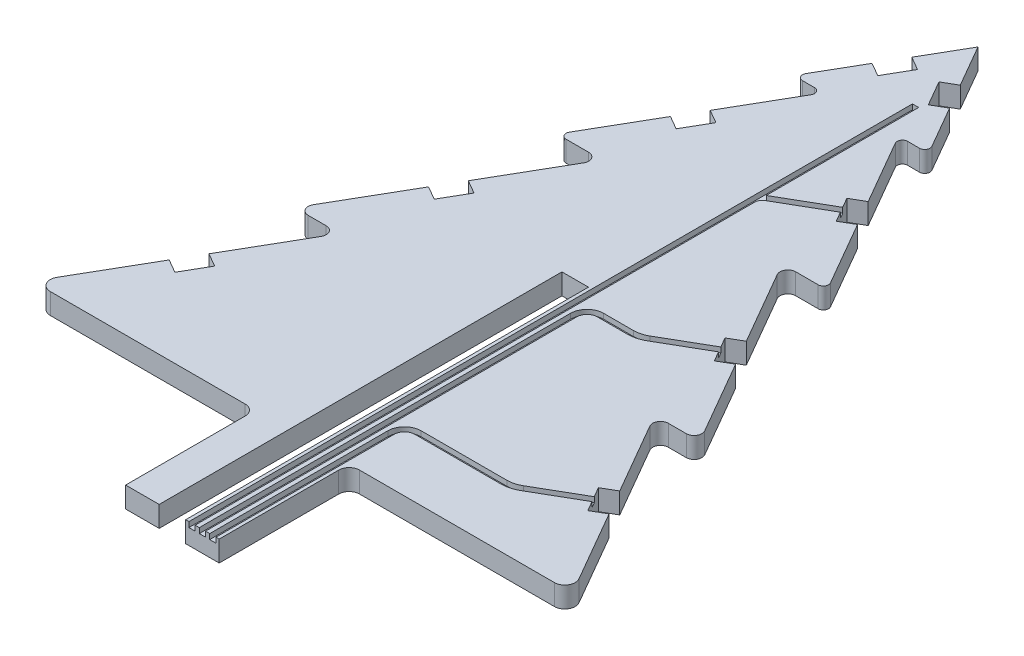
SolidWorks part; units mm, degrees
ref_plane "Plano frontal" through (0, 0, 0) normal (0, 0, 1) x (1, 0, 0)
ref_plane "Plano superior" through (0, 0, 0) normal (0, 1, 0) x (1, 0, 0)
ref_plane "Plano direito" through (0, 0, 0) normal (1, 0, 0) x (0, 0, -1)
sketch "Esboço1" plane through (0, 0, 0) normal (0, 1, 0) x (1, 0, 0)
  line L0 (0, 16.1772) -> (0, -226.058) construction
  line L1 (-9, -140) -> (9, -140)
  line L2 (0, -25) -> (-51.9615, -115)
  line L3 (-51.9615, -115) -> (51.9615, -115)
  line L4 (51.9615, -115) -> (0, -25)
  line L5 (0, 15) -> (-12.9904, -7.5)
  line L6 (-12.9904, -7.5) -> (12.9904, -7.5)
  line L7 (12.9904, -7.5) -> (0, 15)
  line L8 (0, 5) -> (-25.9808, -40)
  line L9 (-25.9808, -40) -> (25.9808, -40)
  line L10 (25.9808, -40) -> (0, 5)
  line L11 (0, -10) -> (-38.9711, -77.5)
  line L12 (-38.9711, -77.5) -> (38.9711, -77.5)
  line L13 (38.9711, -77.5) -> (0, -10)
  line L14 (-9, -140) -> (-9, -115)
  line L15 (9, -140) -> (9, -115)
  circle A0 centre (0, 0) radius 7.5 construction
  circle A1 centre (0, -25) radius 15 construction
  circle A2 centre (0, -55) radius 22.5 construction
  circle A3 centre (0, -85) radius 30 construction
  point P6 (0, 0)
  point P9 (0, -10)
  point P28 (0, -140)
  dimension "D2" = 15
  dimension "D6" = 30
  dimension "D9" = 45
  dimension "D11" = 60
  dimension "D1" = 0
  dimension "D3" = 25
  dimension "D4" = 90
  dimension "D5" = 90
  dimension "D7" = 30
  dimension "D8" = 90
  dimension "D10" = 90
  dimension "D12" = 30
  dimension "D13" = 18
  dimension "D14" = 55
extrude "Árvore" add sketch "Esboço1" along normal blind 4 contours L1 L15 L3 L14 | L12 L2 L3 L4 | L2 L12 L4 L9 | L9 L13 L11 L2 L4 | L12 L13 L9 L4 | L2 L9 L4 | L11 L12 L2 L9 | L13 L9 L10 L6 L8 L11 | L6 L10 L8 | L10 L6 L7 L5 L8
sketch "Esboço2" plane through (0, 4, 0) normal (0, 1, 0) x (1, 0, 0)
  line L0 (0, -33.105) -> (0, 19.5477) construction
  line L1 (0, 19.5477) -> (0, -147.1319) construction
  line L2 (-9, -140) -> (9, -140) construction
  line L3 (-2.55, -62.5) -> (2.55, -62.5)
  line L4 (-2.55, -62.5) -> (-2.55, -140)
  line L5 (-2.55, -140) -> (2.55, -140)
  line L6 (2.55, -62.5) -> (2.55, -140)
  line L7 (-2.55, -62.5) -> (2.55, -140) construction
  line L8 (-2.55, -140) -> (2.55, -62.5) construction
  point P3 (0, -101.25)
  dimension "D1" = 77.5
  dimension "D2" = 5.1
extrude "Encaixe" cut sketch "Esboço2" against normal blind 5
fillet "Filete2" radius 1 1 edges at (12.9904, 2, 7.5)
fillet "Filete3" radius 1 1 edges at (-12.9904, 2, 7.5)
fillet "Filete4" radius 1 1 edges at (-7.2169, 2, 7.5)
fillet "Filete5" radius 1 1 edges at (7.2169, 2, 7.5)
fillet "Filete6" radius 1 1 edges at (25.9808, 2, 40)
fillet "Filete7" radius 1 1 edges at (-25.9808, 2, 40)
fillet "Filete8" radius 1.5 1 edges at (17.3205, 2, 40)
fillet "Filete9" radius 1.5 1 edges at (-17.3205, 2, 40)
fillet "Filete10" radius 1.5 1 edges at (38.9711, 2, 77.5)
fillet "Filete11" radius 1.5 1 edges at (-38.9711, 2, 77.5)
fillet "Filete12" radius 2 1 edges at (51.9615, 2, 115)
fillet "Filete13" radius 2 1 edges at (-51.9615, 2, 115)
fillet "Filete14" radius 2 1 edges at (9, 2, 115)
fillet "Filete15" radius 2 1 edges at (-9, 2, 115)
fillet "Filete16" radius 1.5 1 edges at (30.3109, 2, 77.5)
fillet "Filete17" radius 1.5 1 edges at (-30.3109, 2, 77.5)
sketch "Esboço5" plane through (0, 4, 0) normal (0, 1, 0) x (1, 0, 0)
  line L0 (42.3195, -98.2995) -> (39.5195, -93.4497)
  line L1 (42.3195, -98.2995) -> (39.7214, -99.7995)
  line L2 (39.5195, -93.4497) -> (36.9214, -94.9497)
  line L3 (39.7214, -99.7995) -> (36.9214, -94.9497)
  line L4 (50.2295, -112) -> (31.6099, -79.75) construction
  line L5 (29.5446, -61.1728) -> (26.7446, -56.323)
  line L6 (29.5446, -61.1728) -> (26.9465, -62.6728)
  line L7 (26.7446, -56.323) -> (24.1465, -57.823)
  line L8 (26.9465, -62.6728) -> (24.1465, -57.823)
  line L9 (37.6721, -75.25) -> (18.6195, -42.25) construction
  line L10 (17.9997, -26.1765) -> (15.1997, -21.3267)
  line L11 (17.9997, -26.1765) -> (15.4017, -27.6765)
  line L12 (15.1997, -21.3267) -> (12.6017, -22.8267)
  line L13 (15.4017, -27.6765) -> (12.6017, -22.8267)
  line L14 (25.1147, -38.5) -> (8.0829, -9) construction
  line L15 (7.4619, 2.0757) -> (4.6619, 6.9254)
  line L16 (7.4619, 2.0757) -> (4.8638, 0.5757)
  line L17 (4.6619, 6.9254) -> (2.0638, 5.4254)
  line L18 (4.8638, 0.5757) -> (2.0638, 5.4254)
  line L19 (12.1244, -6) -> (0, 15) construction
  line L20 (0, 20.6146) -> (0, -144.6406) construction
  line L21 (-7.4619, 2.0757) -> (-4.6619, 6.9254)
  line L22 (-7.4619, 2.0757) -> (-4.8638, 0.5757)
  line L23 (-4.8638, 0.5757) -> (-2.0638, 5.4254)
  line L24 (-4.6619, 6.9254) -> (-2.0638, 5.4254)
  line L25 (-17.9997, -26.1765) -> (-15.1997, -21.3267)
  line L26 (-17.9997, -26.1765) -> (-15.4017, -27.6765)
  line L27 (-15.4017, -27.6765) -> (-12.6017, -22.8267)
  line L28 (-15.1997, -21.3267) -> (-12.6017, -22.8267)
  line L29 (-29.5446, -61.1728) -> (-26.7446, -56.323)
  line L30 (-29.5446, -61.1728) -> (-26.9465, -62.6728)
  line L31 (-26.9465, -62.6728) -> (-24.1465, -57.823)
  line L32 (-26.7446, -56.323) -> (-24.1465, -57.823)
  line L33 (-42.3195, -98.2995) -> (-39.5195, -93.4497)
  line L34 (-42.3195, -98.2995) -> (-39.7214, -99.7995)
  line L35 (-39.7214, -99.7995) -> (-36.9214, -94.9497)
  line L36 (-39.5195, -93.4497) -> (-36.9214, -94.9497)
  dimension "D1" = 5.6
  dimension "D2" = 3
  dimension "D3" = 15.82
  dimension "D4" = 3
  dimension "D5" = 5.6
  dimension "D6" = 16.255
  dimension "D7" = 3
  dimension "D8" = 5.6
  dimension "D9" = 14.23
  dimension "D10" = 3
  dimension "D11" = 5.6
  dimension "D12" = 9.325
extrude "Cortes do Led" cut sketch "Esboço5" against normal blind 10
sketch "Esboço6" plane through (0, 4, 0) normal (0, 1, 0) x (1, 0, 0)
  line L0 (2.55, -140) -> (9, -140) construction
  line L1 (3.175, -140) -> (4.375, -140)
  line L2 (3.175, -140) -> (3.175, -0.7885)
  line L3 (3.175, -0.7885) -> (4.375, -0.7885)
  line L4 (4.375, -140) -> (4.375, -0.7885)
  line L5 (2.55, -140) -> (2.55, -62.5) construction
  line L6 (5.175, -140) -> (6.375, -140)
  line L7 (5.175, -140) -> (5.175, -68.5981)
  line L8 (5.175, -68.5981) -> (6.375, -68.5981)
  line L9 (6.375, -140) -> (6.375, -68.5981)
  line L10 (7.175, -140) -> (8.375, -140)
  line L11 (7.175, -140) -> (7.175, -105.7249)
  line L12 (7.175, -105.7249) -> (8.375, -105.7249)
  line L13 (8.375, -140) -> (8.375, -105.7249)
  line L14 (36.9214, -94.9497) -> (39.7214, -99.7995) construction
  line L15 (38.0214, -96.855) -> (38.6214, -97.8942)
  line L16 (38.0214, -96.855) -> (29.3611, -101.855)
  line L17 (38.6214, -97.8942) -> (29.9611, -102.8942)
  line L19 (25.2465, -59.7283) -> (25.8465, -60.7675)
  line L20 (25.2465, -59.7283) -> (16.5863, -64.7283)
  line L21 (25.8465, -60.7675) -> (17.1863, -65.7675)
  line L22 (16.5863, -64.7283) -> (17.1863, -65.7675)
  line L23 (24.1465, -57.823) -> (26.9465, -62.6728) construction
  line L24 (13.7017, -24.732) -> (14.3017, -25.7712)
  line L25 (13.7017, -24.732) -> (3.3094, -30.732)
  line L26 (14.3017, -25.7712) -> (3.9094, -31.7712)
  line L27 (3.3094, -30.732) -> (3.9094, -31.7712)
  line L28 (12.6017, -22.8267) -> (15.4017, -27.6765) construction
  line L29 (3.1638, 3.5202) -> (3.7638, 2.4809)
  line L30 (3.1638, 3.5202) -> (1.7898, 2.7269)
  line L31 (3.7638, 2.4809) -> (2.3898, 1.6877)
  line L32 (1.7898, 2.7269) -> (2.3898, 1.6877)
  line L33 (2.0638, 5.4254) -> (4.8638, 0.5757) construction
  line L34 (29.3611, -101.855) -> (29.9611, -102.8942)
  line L35 (10.375, -102.5249) -> (26.8611, -102.5249)
  line L36 (10.375, -102.5249) -> (10.375, -103.7249)
  line L37 (10.375, -103.7249) -> (26.8611, -103.7249)
  line L38 (26.8611, -102.5249) -> (26.8611, -103.7249)
  line L41 (8.375, -66.5981) -> (14.0863, -66.5981)
  line L42 (8.375, -66.5981) -> (8.375, -65.3981)
  line L43 (8.375, -65.3981) -> (14.0863, -65.3981)
  line L44 (14.0863, -66.5981) -> (14.0863, -65.3981)
  arc A0 (10.375, -102.5249) -> (7.175, -105.7249) centre (10.375, -105.7249) ccw
  arc A1 (10.375, -103.7249) -> (8.375, -105.7249) centre (10.375, -105.7249) ccw
  arc A2 (8.375, -65.3981) -> (5.175, -68.5981) centre (8.375, -68.5981) ccw
  arc A3 (8.375, -66.5981) -> (6.375, -68.5981) centre (8.375, -68.5981) ccw
  arc A4 (26.8611, -102.5249) -> (29.3611, -101.855) centre (26.8611, -97.5249) ccw
  arc A5 (26.8611, -103.7249) -> (29.9611, -102.8942) centre (26.8611, -97.5249) ccw
  arc A6 (14.0863, -65.3981) -> (16.5863, -64.7283) centre (14.0863, -60.3981) ccw
  arc A7 (14.0863, -66.5981) -> (17.1863, -65.7675) centre (14.0863, -60.3981) ccw
  dimension "D19" = 5
  dimension "D21" = 2
  dimension "D22" = 3.2
  dimension "D24" = 2
  dimension "D25" = 3.2
  dimension "D20" = 1.2
  dimension "D23" = 5
  dimension "D26" = 6.2
  dimension "D1" = 1.2
  dimension "D2" = 1.2
  dimension "D3" = 1.2
  dimension "D4" = 0.8
  dimension "D5" = 0.8
  dimension "D6" = 0.625
  dimension "D7" = 1.2
  dimension "D8" = 2.2
  dimension "D9" = 1.2
  dimension "D10" = 2.2
  dimension "D11" = 1.2
  dimension "D12" = 2.2
  dimension "D13" = 1.2
  dimension "D14" = 2.2
  dimension "D15" = 12
  dimension "D16" = 10
  dimension "D17" = 10
  dimension "D18" = 1.2
extrude "Corte-extrusão4" cut sketch "Esboço6" against normal blind 1 contours L38 A5 L34 A4 | L38 L35 L36 L37 | L16 L34 L17 L15 | A1 L36 A0 L12 | L10 L13 L12 L11 | L20 L22 L21 L19 | L44 A7 L22 A6 | L41 L44 L43 L42 | A3 L42 A2 L8 | L6 L9 L8 L7 | L26 L24 L25 L4 | L27 L25 L4 L3 L2 L1 L26 | L25 L27 L26 L4
fillet "Filete18" radius 1.5 1 edges at (4.375, 3.5, 31.5024)
